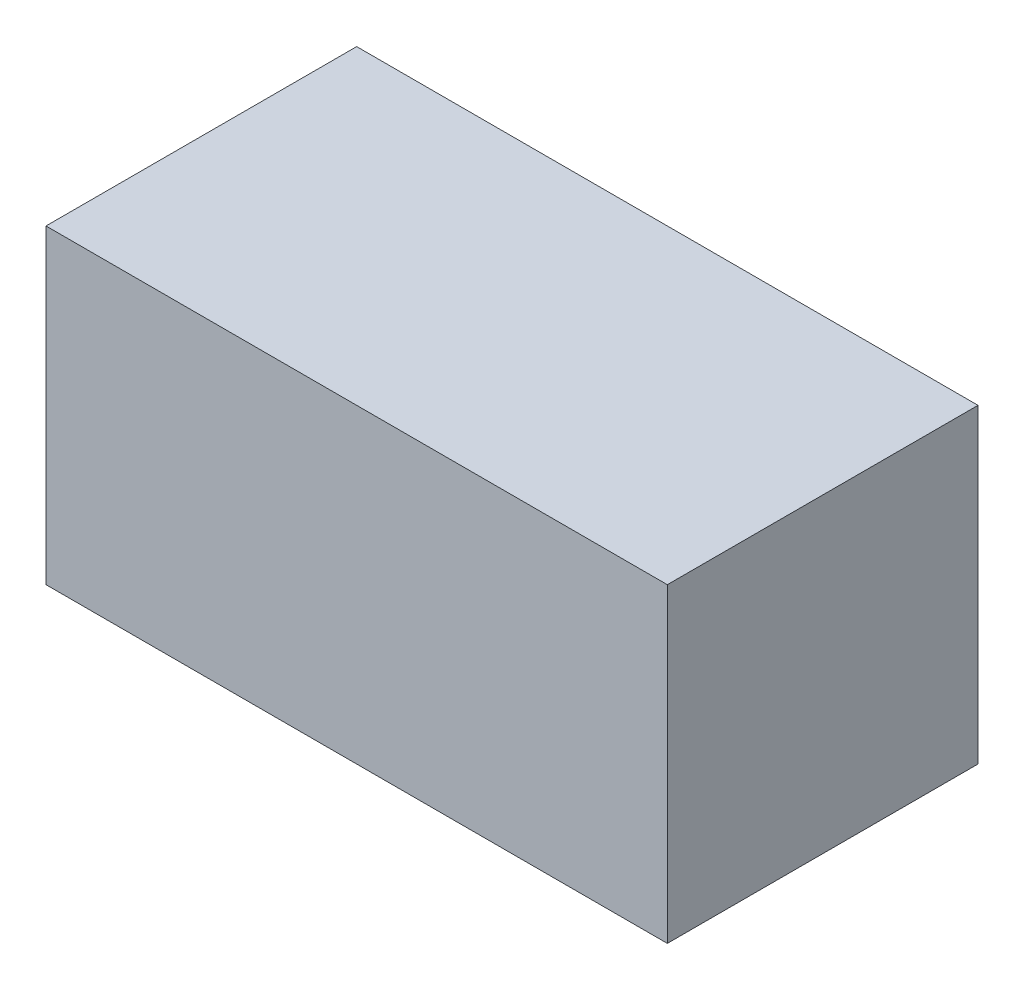
SolidWorks part; units mm, degrees
ref_plane "Front Plane" through (0, 0, 0) normal (0, 0, 1) x (1, 0, 0)
ref_plane "Top Plane" through (0, 0, 0) normal (0, 1, 0) x (1, 0, 0)
ref_plane "Right Plane" through (0, 0, 0) normal (1, 0, 0) x (0, 0, -1)
sketch "Sketch1" plane through (0, 0, 0) normal (0, 0, 1) x (1, 0, 0)
  line L1 (0, 0) -> (20, 0)
  line L2 (0, 0) -> (0, 10)
  line L3 (0, 10) -> (20, 10)
  line L4 (20, 0) -> (20, 10)
  dimension "D1" = 10
  dimension "D2" = 20
extrude "Boss-Extrude1" add sketch "Sketch1" along normal blind 10 from offset 5 offset against normal yes
